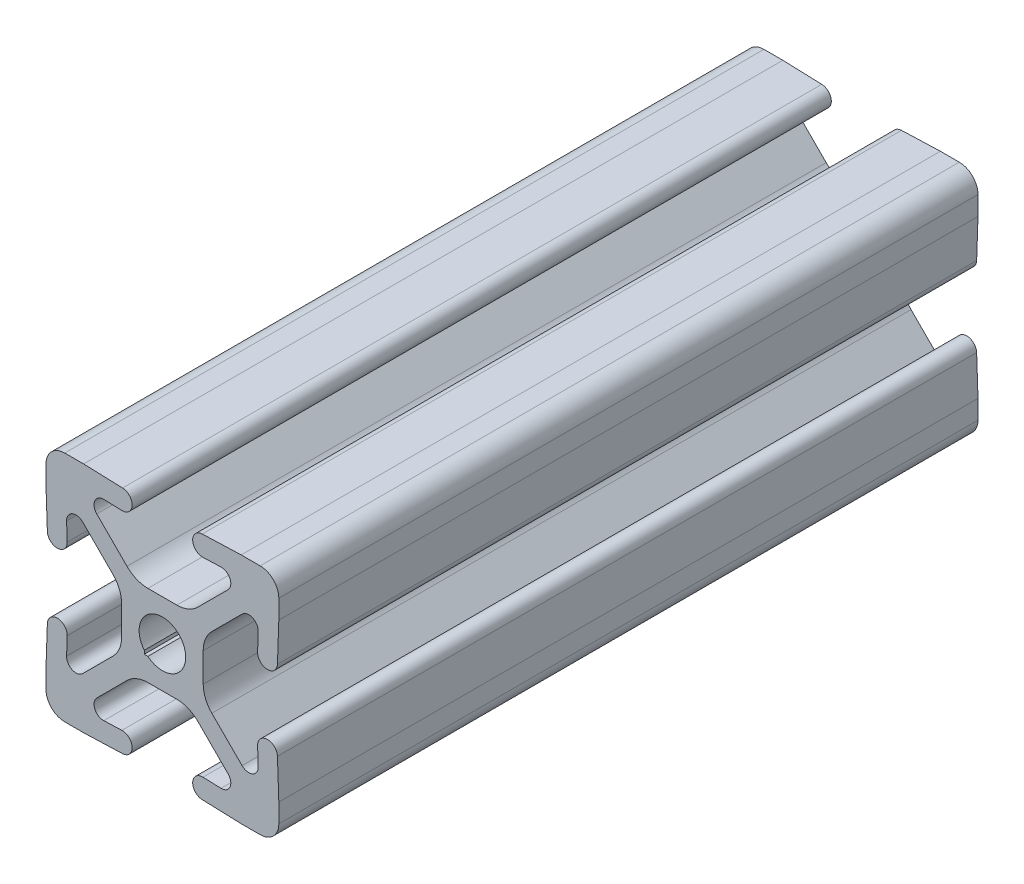
SolidWorks part; units mm, degrees
ref_plane "Front Plane" through (0, 0, 0) normal (0, 0, 1) x (1, 0, 0)
ref_plane "Top Plane" through (0, 0, 0) normal (0, 1, 0) x (1, 0, 0)
ref_plane "Right Plane" through (0, 0, 0) normal (1, 0, 0) x (0, 0, -1)
sketch "Model" plane through (0, 0, 0) normal (0, 0, 1) x (1, 0, 0)
  line L38 (50.6495, 75.4336) -> (50.2699, 75.4336)
  line L39 (50.2699, 75.4336) -> (50.2699, 75.8133)
  line L40 (50.66, 72.9999) -> (53.7746, 72.9999)
  line L41 (56.0196, 72.0699) -> (59.2642, 68.8254)
  line L42 (58.5103, 67.0916) -> (56.5725, 67.1592)
  line L43 (56.498, 65.0269) -> (60.6773, 64.881)
  line L44 (60.6773, 64.881) -> (62.7107, 64.881)
  line L45 (64.7173, 66.8876) -> (64.7173, 68.921)
  line L46 (64.7173, 68.921) -> (64.5713, 73.1002)
  line L47 (62.439, 73.0257) -> (62.5067, 71.0879)
  line L48 (60.7729, 70.334) -> (57.5283, 73.5786)
  line L49 (56.5984, 75.8237) -> (56.5984, 78.9383)
  line L50 (57.5283, 81.1833) -> (60.7729, 84.4279)
  line L51 (62.5067, 83.674) -> (62.439, 81.7362)
  line L52 (64.5713, 81.6617) -> (64.7173, 85.841)
  line L53 (64.7173, 85.841) -> (64.7173, 87.8744)
  line L54 (62.7107, 89.881) -> (60.6773, 89.881)
  line L55 (60.6773, 89.881) -> (56.498, 89.735)
  line L56 (56.5725, 87.6027) -> (58.5103, 87.6704)
  line L57 (59.2642, 85.9366) -> (56.0196, 82.692)
  line L58 (53.7746, 81.7621) -> (50.66, 81.7621)
  line L59 (48.4149, 82.692) -> (45.1703, 85.9366)
  line L60 (45.9242, 87.6704) -> (47.862, 87.6027)
  line L61 (47.9365, 89.735) -> (43.7573, 89.881)
  line L62 (43.7573, 89.881) -> (41.7239, 89.881)
  line L63 (39.7173, 87.8744) -> (39.7173, 85.841)
  line L64 (39.7173, 85.841) -> (39.8632, 81.6617)
  line L65 (41.9955, 81.7362) -> (41.9278, 83.674)
  line L66 (43.6616, 84.4279) -> (46.9062, 81.1833)
  line L67 (47.8361, 78.9383) -> (47.8361, 75.8237)
  line L68 (46.9062, 73.5786) -> (43.6616, 70.334)
  line L69 (41.9278, 71.0879) -> (41.9955, 73.0257)
  line L70 (39.8632, 73.1002) -> (39.7173, 68.921)
  line L71 (39.7173, 68.921) -> (39.7173, 66.8876)
  line L72 (41.7239, 64.881) -> (43.7573, 64.881)
  line L73 (43.7573, 64.881) -> (47.9365, 65.0269)
  line L74 (47.862, 67.1592) -> (45.9242, 67.0916)
  line L75 (45.1703, 68.8254) -> (48.4149, 72.0699)
  arc A29 (50.6495, 75.4336) -> (50.2699, 75.8133) centre (52.2173, 77.381) ccw
  arc A30 (56.0196, 72.0699) -> (53.7746, 72.9999) centre (53.7746, 69.8249) ccw
  arc A31 (58.5103, 67.0916) -> (59.2642, 68.8254) centre (58.5458, 68.1069) ccw
  arc A32 (56.5725, 67.1592) -> (56.498, 65.0269) centre (56.5353, 66.0931) ccw
  arc A33 (62.7107, 64.881) -> (64.7173, 66.8876) centre (62.7107, 66.8876) ccw
  arc A34 (64.5713, 73.1002) -> (62.439, 73.0257) centre (63.5052, 73.063) ccw
  arc A35 (60.7729, 70.334) -> (62.5067, 71.0879) centre (61.4913, 71.0525) ccw
  arc A36 (56.5984, 75.8237) -> (57.5283, 73.5786) centre (59.7734, 75.8237) ccw
  arc A37 (57.5283, 81.1833) -> (56.5984, 78.9383) centre (59.7734, 78.9383) ccw
  arc A38 (62.5067, 83.674) -> (60.7729, 84.4279) centre (61.4913, 83.7095) ccw
  arc A39 (62.439, 81.7362) -> (64.5713, 81.6617) centre (63.5052, 81.699) ccw
  arc A40 (64.7173, 87.8744) -> (62.7107, 89.881) centre (62.7107, 87.8744) ccw
  arc A41 (56.498, 89.735) -> (56.5725, 87.6027) centre (56.5353, 88.6689) ccw
  arc A42 (59.2642, 85.9366) -> (58.5103, 87.6704) centre (58.5458, 86.655) ccw
  arc A43 (53.7746, 81.7621) -> (56.0196, 82.692) centre (53.7746, 84.9371) ccw
  arc A44 (48.4149, 82.692) -> (50.66, 81.7621) centre (50.66, 84.9371) ccw
  arc A45 (45.9242, 87.6704) -> (45.1703, 85.9366) centre (45.8887, 86.655) ccw
  arc A46 (47.862, 87.6027) -> (47.9365, 89.735) centre (47.8993, 88.6689) ccw
  arc A47 (41.7239, 89.881) -> (39.7173, 87.8744) centre (41.7239, 87.8744) ccw
  arc A48 (39.8632, 81.6617) -> (41.9955, 81.7362) centre (40.9293, 81.699) ccw
  arc A49 (43.6616, 84.4279) -> (41.9278, 83.674) centre (42.9432, 83.7095) ccw
  arc A50 (47.8361, 78.9383) -> (46.9062, 81.1833) centre (44.6611, 78.9383) ccw
  arc A51 (46.9062, 73.5786) -> (47.8361, 75.8237) centre (44.6611, 75.8237) ccw
  arc A52 (41.9278, 71.0879) -> (43.6616, 70.334) centre (42.9432, 71.0525) ccw
  arc A53 (41.9955, 73.0257) -> (39.8632, 73.1002) centre (40.9293, 73.063) ccw
  arc A54 (39.7173, 66.8876) -> (41.7239, 64.881) centre (41.7239, 66.8876) ccw
  arc A55 (47.9365, 65.0269) -> (47.862, 67.1592) centre (47.8993, 66.0931) ccw
  arc A56 (45.1703, 68.8254) -> (45.9242, 67.0916) centre (45.8887, 68.1069) ccw
  arc A57 (50.66, 72.9999) -> (48.4149, 72.0699) centre (50.66, 69.8249) ccw
extrude "Boss-Extrude1" add sketch "Model" along normal blind 75.0824
